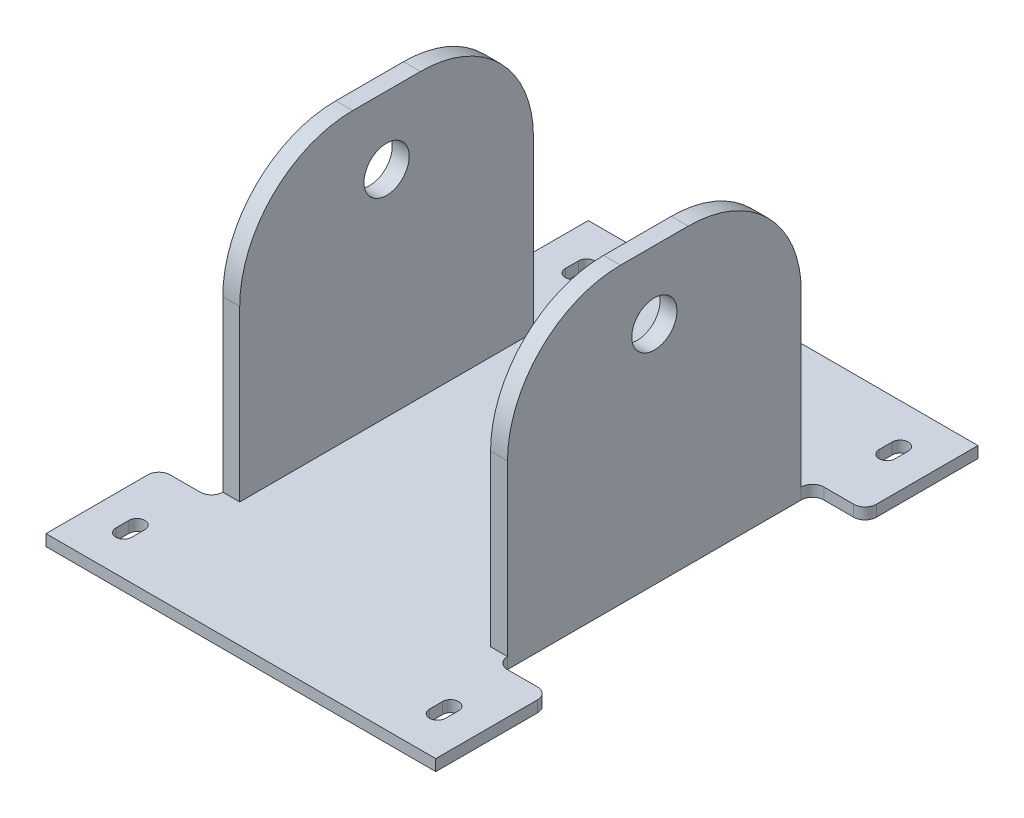
SolidWorks part; units mm, degrees
ref_plane "Front Plane" through (0, 0, 0) normal (0, 0, 1) x (1, 0, 0)
ref_plane "Top Plane" through (0, 0, 0) normal (0, 1, 0) x (1, 0, 0)
ref_plane "Right Plane" through (0, 0, 0) normal (1, 0, 0) x (0, 0, -1)
sketch "Sketch1" plane through (0, 0, 0) normal (0, 1, 0) x (1, 0, 0)
  line L0 (-32.5, 28) -> (-27.204, 28)
  line L1 (-34.5, -48) -> (34.5, -48)
  line L2 (-34.5, -48) -> (-34.5, -30)
  line L3 (-34.5, 48) -> (34.5, 48)
  line L4 (34.5, -48) -> (34.5, -30)
  line L5 (-34.5, -48) -> (34.5, 48) construction
  line L6 (-34.5, 48) -> (34.5, -48) construction
  line L7 (-25.204, 26) -> (-25.204, -26)
  line L8 (-34.5, 0) -> (34.5, 0) construction
  line L9 (0, 48) -> (0, -48) construction
  line L10 (-34.5, 30) -> (-34.5, 48)
  line L11 (-27.7687, 40.9559) -> (-27.7687, 38.6347) construction
  line L12 (-26.3537, 40.9559) -> (-26.3537, 38.6347)
  line L13 (-29.1837, 40.9559) -> (-29.1837, 38.6347)
  line L14 (27.7687, 40.9559) -> (27.7687, 38.6347) construction
  line L15 (26.3537, 40.9559) -> (26.3537, 38.6347)
  line L16 (29.1837, 40.9559) -> (29.1837, 38.6347)
  line L17 (32.5, 28) -> (27.204, 28)
  line L18 (25.204, 26) -> (25.204, -26)
  line L19 (-27.7687, -40.9559) -> (-27.7687, -38.6347) construction
  line L20 (-26.3537, -40.9559) -> (-26.3537, -38.6347)
  line L21 (-29.1837, -40.9559) -> (-29.1837, -38.6347)
  line L22 (27.7687, -40.9559) -> (27.7687, -38.6347) construction
  line L23 (26.3537, -40.9559) -> (26.3537, -38.6347)
  line L24 (29.1837, -40.9559) -> (29.1837, -38.6347)
  line L25 (32.5, -28) -> (27.204, -28)
  line L26 (-32.5, -28) -> (-27.204, -28)
  line L27 (34.5, 30) -> (34.5, 48)
  arc A0 (-25.204, 26) -> (-27.204, 28) centre (-27.204, 26) ccw
  arc A1 (-34.5, 30) -> (-32.5, 28) centre (-32.5, 30) ccw
  arc A3 (-26.3537, 40.9559) -> (-29.1837, 40.9559) centre (-27.7687, 40.9559) ccw
  arc A4 (-29.1837, 38.6347) -> (-26.3537, 38.6347) centre (-27.7687, 38.6347) ccw
  arc A5 (26.3537, 40.9559) -> (29.1837, 40.9559) centre (27.7687, 40.9559) cw
  arc A6 (29.1837, 38.6347) -> (26.3537, 38.6347) centre (27.7687, 38.6347) cw
  arc A7 (25.204, 26) -> (27.204, 28) centre (27.204, 26) cw
  arc A8 (34.5, 30) -> (32.5, 28) centre (32.5, 30) cw
  arc A9 (-26.3537, -40.9559) -> (-29.1837, -40.9559) centre (-27.7687, -40.9559) cw
  arc A10 (-29.1837, -38.6347) -> (-26.3537, -38.6347) centre (-27.7687, -38.6347) cw
  arc A11 (26.3537, -40.9559) -> (29.1837, -40.9559) centre (27.7687, -40.9559) ccw
  arc A12 (29.1837, -38.6347) -> (26.3537, -38.6347) centre (27.7687, -38.6347) ccw
  arc A13 (25.204, -26) -> (27.204, -28) centre (27.204, -26) ccw
  arc A14 (34.5, -30) -> (32.5, -28) centre (32.5, -30) ccw
  arc A15 (-25.204, -26) -> (-27.204, -28) centre (-27.204, -26) cw
  arc A16 (-34.5, -30) -> (-32.5, -28) centre (-32.5, -30) cw
  point P0 (0, 0)
  point P17 (-34.5, 28)
  point P20 (-27.7687, 39.7953)
  point P30 (27.7687, 39.7953)
  point P44 (-27.7687, -39.7953)
  point P51 (27.7687, -39.7953)
  point P62 (25.204, 0)
  point P65 (-25.204, 0)
  dimension "D3" = 2
  dimension "D4" = 2
  dimension "D6" = 20
  dimension "D1" = 96
  dimension "D2" = 69
extrude "Boss-Extrude1" add sketch "Sketch1" along normal blind 2
sketch "Sketch2" plane through (0, 2, 0) normal (0, 1, 0) x (1, 0, 0)
  line L0 (0, 0) -> (0, 35.2203) construction
  line L1 (-25.204, 26) -> (-22.204, 26)
  line L2 (-25.204, 26) -> (-25.204, -26)
  line L3 (-25.204, -26) -> (-22.204, -26)
  line L4 (-22.204, 26) -> (-22.204, -26)
  line L5 (25.204, -26) -> (22.204, -26)
  line L6 (22.204, 26) -> (22.204, -26)
  line L7 (25.204, 26) -> (22.204, 26)
  line L8 (25.204, 26) -> (25.204, -26)
  line L9 (-25.204, 26) -> (-25.204, -26) construction
  dimension "D1" = 3
extrude "Boss-Extrude2" add sketch "Sketch2" along normal blind 50
sketch "Sketch3" plane through (-25.204, 0, 0) normal (-1, 0, 0) x (0, 0, 1)
  line L0 (-26, 0) -> (26, 0) construction
  line L1 (0, 40) -> (0, 52) construction
  line L7 (-26, 0) -> (26, 0)
  line L8 (26, 0) -> (26, 2)
  line L9 (26, 2) -> (26, 52)
  line L10 (26, 52) -> (-26, 52)
  line L11 (-26, 52) -> (-26, 2)
  line L12 (-26, 2) -> (-26, 0)
  line L13 (-26, 0) -> (26, 0)
  line L14 (26, 0) -> (26, 2)
  line L15 (26, 2) -> (26, 52)
  line L16 (26, 52) -> (-6, 52)
  line L17 (-26, 32) -> (-26, 2)
  line L18 (-26, 2) -> (-26, 0)
  circle A0 centre (0, 40) radius 4
  arc A1 (-26, 32) -> (-6, 52) centre (-6, 32) cw
  arc A2 (26, 32) -> (6, 52) centre (6, 32) ccw
  dimension "D3" = 20
  dimension "D4" = 8
  dimension "D1" = 40
  dimension "D2" = 0
extrude "Cut-Extrude1" cut sketch "Sketch3" against normal blind 90
